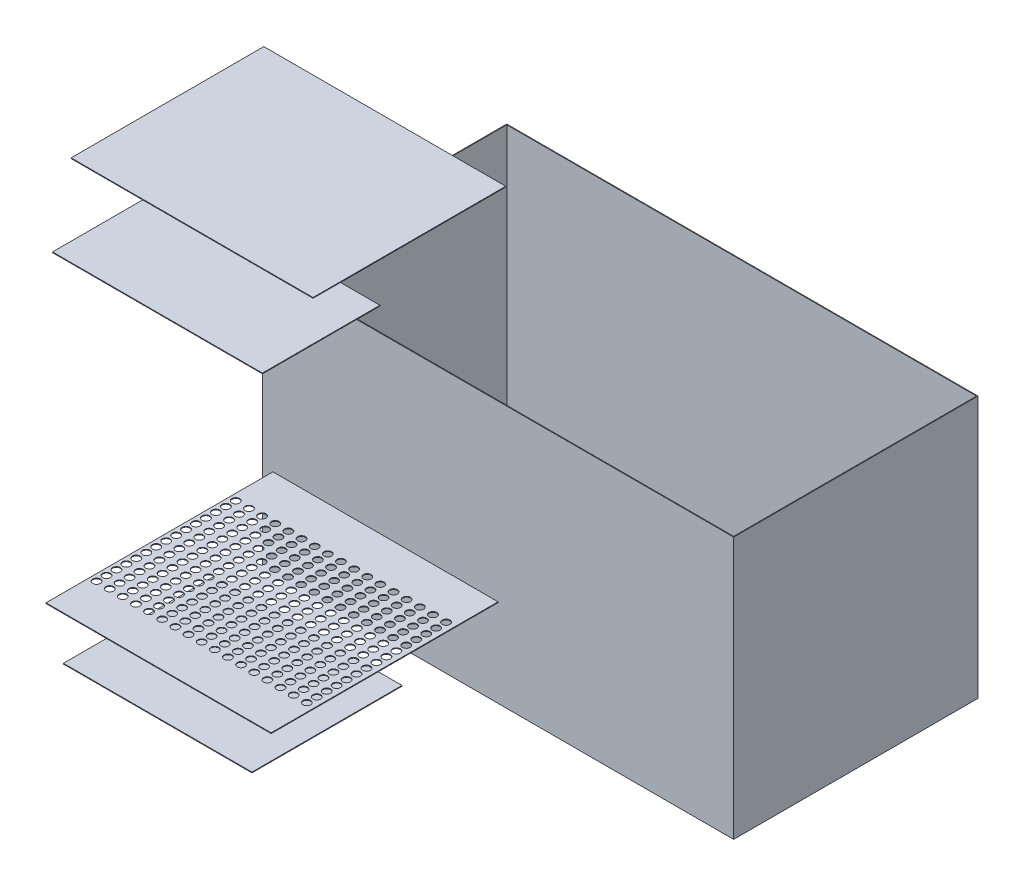
SolidWorks part; units mm, degrees
ref_plane "Спереди" through (0, 0, 0) normal (0, 0, 1) x (1, 0, 0)
ref_plane "Сверху" through (0, 0, 0) normal (0, 1, 0) x (1, 0, 0)
ref_plane "Справа" through (0, 0, 0) normal (1, 0, 0) x (0, 0, -1)
sketch "MASTER_FOOTPRINT" plane through (0, 0, 0) normal (0, 1, 0) x (1, 0, 0)
  line L1 (0, 0) -> (1350, 0)
  line L2 (0, 0) -> (0, 700)
  line L3 (0, 700) -> (1350, 700)
  line L4 (1350, 0) -> (1350, 700)
  dimension "D1" = 1350
  dimension "D2" = 700
extrude "BATH_BASE_PLATE" add sketch "MASTER_FOOTPRINT" along normal blind 750
shell "BATH_SHELL_2MM" thickness 2
sketch "Эскиз1" plane through (0, 0, 0) normal (0, 1, 0) x (1, 0, 0)
  line L1 (80, -220) -> (620, -220)
  line L2 (80, -220) -> (80, -650)
  line L3 (80, -650) -> (620, -650)
  line L4 (620, -220) -> (620, -650)
extrude "INLET_IMPACT_BAFFLE" add sketch "Эскиз1" along normal blind 2 from offset 125 separate body
sketch "Эскиз2" plane through (0, 0, 0) normal (0, 1, 0) x (1, 0, 0)
  line L0 (2, 2) -> (1348, 2) construction
  line L1 (30, 2) -> (675, 2)
  line L2 (30, 2) -> (30, -650)
  line L3 (30, -650) -> (675, -650)
  line L4 (675, 2) -> (675, -650)
  circle A0 centre (48.8235, -125) radius 11
  circle A1 centre (48.8235, -153.5) radius 11
  circle A2 centre (48.8235, -182) radius 11
  circle A3 centre (48.8235, -210.5) radius 11
  circle A4 centre (48.8235, -239) radius 11
  circle A5 centre (48.8235, -267.5) radius 11
  circle A6 centre (48.8235, -296) radius 11
  circle A7 centre (48.8235, -324.5) radius 11
  circle A8 centre (48.8235, -353) radius 11
  circle A9 centre (48.8235, -381.5) radius 11
  circle A10 centre (48.8235, -410) radius 11
  circle A11 centre (48.8235, -438.5) radius 11
  circle A12 centre (48.8235, -467) radius 11
  circle A13 centre (48.8235, -495.5) radius 11
  circle A14 centre (48.8235, -524) radius 11
  circle A15 centre (86.4706, -125) radius 11
  circle A16 centre (86.4706, -153.5) radius 11
  circle A17 centre (86.4706, -182) radius 11
  circle A18 centre (86.4706, -210.5) radius 11
  circle A19 centre (86.4706, -239) radius 11
  circle A20 centre (86.4706, -267.5) radius 11
  circle A21 centre (86.4706, -296) radius 11
  circle A22 centre (86.4706, -324.5) radius 11
  circle A23 centre (86.4706, -353) radius 11
  circle A24 centre (86.4706, -381.5) radius 11
  circle A25 centre (86.4706, -410) radius 11
  circle A26 centre (86.4706, -438.5) radius 11
  circle A27 centre (86.4706, -467) radius 11
  circle A28 centre (86.4706, -495.5) radius 11
  circle A29 centre (86.4706, -524) radius 11
  circle A30 centre (124.1176, -125) radius 11
  circle A31 centre (124.1176, -153.5) radius 11
  circle A32 centre (124.1176, -182) radius 11
  circle A33 centre (124.1176, -210.5) radius 11
  circle A34 centre (124.1176, -239) radius 11
  circle A35 centre (124.1176, -267.5) radius 11
  circle A36 centre (124.1176, -296) radius 11
  circle A37 centre (124.1176, -324.5) radius 11
  circle A38 centre (124.1176, -353) radius 11
  circle A39 centre (124.1176, -381.5) radius 11
  circle A40 centre (124.1176, -410) radius 11
  circle A41 centre (124.1176, -438.5) radius 11
  circle A42 centre (124.1176, -467) radius 11
  circle A43 centre (124.1176, -495.5) radius 11
  circle A44 centre (124.1176, -524) radius 11
  circle A45 centre (161.7647, -125) radius 11
  circle A46 centre (161.7647, -153.5) radius 11
  circle A47 centre (161.7647, -182) radius 11
  circle A48 centre (161.7647, -210.5) radius 11
  circle A49 centre (161.7647, -239) radius 11
  circle A50 centre (161.7647, -267.5) radius 11
  circle A51 centre (161.7647, -296) radius 11
  circle A52 centre (161.7647, -324.5) radius 11
  circle A53 centre (161.7647, -353) radius 11
  circle A54 centre (161.7647, -381.5) radius 11
  circle A55 centre (161.7647, -410) radius 11
  circle A56 centre (161.7647, -438.5) radius 11
  circle A57 centre (161.7647, -467) radius 11
  circle A58 centre (161.7647, -495.5) radius 11
  circle A59 centre (161.7647, -524) radius 11
  circle A60 centre (199.4118, -125) radius 11
  circle A61 centre (199.4118, -153.5) radius 11
  circle A62 centre (199.4118, -182) radius 11
  circle A63 centre (199.4118, -210.5) radius 11
  circle A64 centre (199.4118, -239) radius 11
  circle A65 centre (199.4118, -267.5) radius 11
  circle A66 centre (199.4118, -296) radius 11
  circle A67 centre (199.4118, -324.5) radius 11
  circle A68 centre (199.4118, -353) radius 11
  circle A69 centre (199.4118, -381.5) radius 11
  circle A70 centre (199.4118, -410) radius 11
  circle A71 centre (199.4118, -438.5) radius 11
  circle A72 centre (199.4118, -467) radius 11
  circle A73 centre (199.4118, -495.5) radius 11
  circle A74 centre (199.4118, -524) radius 11
  circle A75 centre (237.0588, -125) radius 11
  circle A76 centre (237.0588, -153.5) radius 11
  circle A77 centre (237.0588, -182) radius 11
  circle A78 centre (237.0588, -210.5) radius 11
  circle A79 centre (237.0588, -239) radius 11
  circle A80 centre (237.0588, -267.5) radius 11
  circle A81 centre (237.0588, -296) radius 11
  circle A82 centre (237.0588, -324.5) radius 11
  circle A83 centre (237.0588, -353) radius 11
  circle A84 centre (237.0588, -381.5) radius 11
  circle A85 centre (237.0588, -410) radius 11
  circle A86 centre (237.0588, -438.5) radius 11
  circle A87 centre (237.0588, -467) radius 11
  circle A88 centre (237.0588, -495.5) radius 11
  circle A89 centre (237.0588, -524) radius 11
  circle A90 centre (274.7059, -125) radius 11
  circle A91 centre (274.7059, -153.5) radius 11
  circle A92 centre (274.7059, -182) radius 11
  circle A93 centre (274.7059, -210.5) radius 11
  circle A94 centre (274.7059, -239) radius 11
  circle A95 centre (274.7059, -267.5) radius 11
  circle A96 centre (274.7059, -296) radius 11
  circle A97 centre (274.7059, -324.5) radius 11
  circle A98 centre (274.7059, -353) radius 11
  circle A99 centre (274.7059, -381.5) radius 11
  circle A100 centre (274.7059, -410) radius 11
  circle A101 centre (274.7059, -438.5) radius 11
  circle A102 centre (274.7059, -467) radius 11
  circle A103 centre (274.7059, -495.5) radius 11
  circle A104 centre (274.7059, -524) radius 11
  circle A105 centre (312.3529, -125) radius 11
  circle A106 centre (312.3529, -153.5) radius 11
  circle A107 centre (312.3529, -182) radius 11
  circle A108 centre (312.3529, -210.5) radius 11
  circle A109 centre (312.3529, -239) radius 11
  circle A110 centre (312.3529, -267.5) radius 11
  circle A111 centre (312.3529, -296) radius 11
  circle A112 centre (312.3529, -324.5) radius 11
  circle A113 centre (312.3529, -353) radius 11
  circle A114 centre (312.3529, -381.5) radius 11
  circle A115 centre (312.3529, -410) radius 11
  circle A116 centre (312.3529, -438.5) radius 11
  circle A117 centre (312.3529, -467) radius 11
  circle A118 centre (312.3529, -495.5) radius 11
  circle A119 centre (312.3529, -524) radius 11
  circle A120 centre (350, -125) radius 11
  circle A121 centre (350, -153.5) radius 11
  circle A122 centre (350, -182) radius 11
  circle A123 centre (350, -210.5) radius 11
  circle A124 centre (350, -239) radius 11
  circle A125 centre (350, -267.5) radius 11
  circle A126 centre (350, -296) radius 11
  circle A127 centre (350, -324.5) radius 11
  circle A128 centre (350, -353) radius 11
  circle A129 centre (350, -381.5) radius 11
  circle A130 centre (350, -410) radius 11
  circle A131 centre (350, -438.5) radius 11
  circle A132 centre (350, -467) radius 11
  circle A133 centre (350, -495.5) radius 11
  circle A134 centre (350, -524) radius 11
  circle A135 centre (387.6471, -125) radius 11
  circle A136 centre (387.6471, -153.5) radius 11
  circle A137 centre (387.6471, -182) radius 11
  circle A138 centre (387.6471, -210.5) radius 11
  circle A139 centre (387.6471, -239) radius 11
  circle A140 centre (387.6471, -267.5) radius 11
  circle A141 centre (387.6471, -296) radius 11
  circle A142 centre (387.6471, -324.5) radius 11
  circle A143 centre (387.6471, -353) radius 11
  circle A144 centre (387.6471, -381.5) radius 11
  circle A145 centre (387.6471, -410) radius 11
  circle A146 centre (387.6471, -438.5) radius 11
  circle A147 centre (387.6471, -467) radius 11
  circle A148 centre (387.6471, -495.5) radius 11
  circle A149 centre (387.6471, -524) radius 11
  circle A150 centre (425.2941, -125) radius 11
  circle A151 centre (425.2941, -153.5) radius 11
  circle A152 centre (425.2941, -182) radius 11
  circle A153 centre (425.2941, -210.5) radius 11
  circle A154 centre (425.2941, -239) radius 11
  circle A155 centre (425.2941, -267.5) radius 11
  circle A156 centre (425.2941, -296) radius 11
  circle A157 centre (425.2941, -324.5) radius 11
  circle A158 centre (425.2941, -353) radius 11
  circle A159 centre (425.2941, -381.5) radius 11
  circle A160 centre (425.2941, -410) radius 11
  circle A161 centre (425.2941, -438.5) radius 11
  circle A162 centre (425.2941, -467) radius 11
  circle A163 centre (425.2941, -495.5) radius 11
  circle A164 centre (425.2941, -524) radius 11
  circle A165 centre (462.9412, -125) radius 11
  circle A166 centre (462.9412, -153.5) radius 11
  circle A167 centre (462.9412, -182) radius 11
  circle A168 centre (462.9412, -210.5) radius 11
  circle A169 centre (462.9412, -239) radius 11
  circle A170 centre (462.9412, -267.5) radius 11
  circle A171 centre (462.9412, -296) radius 11
  circle A172 centre (462.9412, -324.5) radius 11
  circle A173 centre (462.9412, -353) radius 11
  circle A174 centre (462.9412, -381.5) radius 11
  circle A175 centre (462.9412, -410) radius 11
  circle A176 centre (462.9412, -438.5) radius 11
  circle A177 centre (462.9412, -467) radius 11
  circle A178 centre (462.9412, -495.5) radius 11
  circle A179 centre (462.9412, -524) radius 11
  circle A180 centre (500.5882, -125) radius 11
  circle A181 centre (500.5882, -153.5) radius 11
  circle A182 centre (500.5882, -182) radius 11
  circle A183 centre (500.5882, -210.5) radius 11
  circle A184 centre (500.5882, -239) radius 11
  circle A185 centre (500.5882, -267.5) radius 11
  circle A186 centre (500.5882, -296) radius 11
  circle A187 centre (500.5882, -324.5) radius 11
  circle A188 centre (500.5882, -353) radius 11
  circle A189 centre (500.5882, -381.5) radius 11
  circle A190 centre (500.5882, -410) radius 11
  circle A191 centre (500.5882, -438.5) radius 11
  circle A192 centre (500.5882, -467) radius 11
  circle A193 centre (500.5882, -495.5) radius 11
  circle A194 centre (500.5882, -524) radius 11
  circle A195 centre (538.2353, -125) radius 11
  circle A196 centre (538.2353, -153.5) radius 11
  circle A197 centre (538.2353, -182) radius 11
  circle A198 centre (538.2353, -210.5) radius 11
  circle A199 centre (538.2353, -239) radius 11
  circle A200 centre (538.2353, -267.5) radius 11
  circle A201 centre (538.2353, -296) radius 11
  circle A202 centre (538.2353, -324.5) radius 11
  circle A203 centre (538.2353, -353) radius 11
  circle A204 centre (538.2353, -381.5) radius 11
  circle A205 centre (538.2353, -410) radius 11
  circle A206 centre (538.2353, -438.5) radius 11
  circle A207 centre (538.2353, -467) radius 11
  circle A208 centre (538.2353, -495.5) radius 11
  circle A209 centre (538.2353, -524) radius 11
  circle A210 centre (575.8824, -125) radius 11
  circle A211 centre (575.8824, -153.5) radius 11
  circle A212 centre (575.8824, -182) radius 11
  circle A213 centre (575.8824, -210.5) radius 11
  circle A214 centre (575.8824, -239) radius 11
  circle A215 centre (575.8824, -267.5) radius 11
  circle A216 centre (575.8824, -296) radius 11
  circle A217 centre (575.8824, -324.5) radius 11
  circle A218 centre (575.8824, -353) radius 11
  circle A219 centre (575.8824, -381.5) radius 11
  circle A220 centre (575.8824, -410) radius 11
  circle A221 centre (575.8824, -438.5) radius 11
  circle A222 centre (575.8824, -467) radius 11
  circle A223 centre (575.8824, -495.5) radius 11
  circle A224 centre (575.8824, -524) radius 11
  circle A225 centre (613.5294, -125) radius 11
  circle A226 centre (613.5294, -153.5) radius 11
  circle A227 centre (613.5294, -182) radius 11
  circle A228 centre (613.5294, -210.5) radius 11
  circle A229 centre (613.5294, -239) radius 11
  circle A230 centre (613.5294, -267.5) radius 11
  circle A231 centre (613.5294, -296) radius 11
  circle A232 centre (613.5294, -324.5) radius 11
  circle A233 centre (613.5294, -353) radius 11
  circle A234 centre (613.5294, -381.5) radius 11
  circle A235 centre (613.5294, -410) radius 11
  circle A236 centre (613.5294, -438.5) radius 11
  circle A237 centre (613.5294, -467) radius 11
  circle A238 centre (613.5294, -495.5) radius 11
  circle A239 centre (613.5294, -524) radius 11
  circle A240 centre (651.1765, -125) radius 11
  circle A241 centre (651.1765, -153.5) radius 11
  circle A242 centre (651.1765, -182) radius 11
  circle A243 centre (651.1765, -210.5) radius 11
  circle A244 centre (651.1765, -239) radius 11
  circle A245 centre (651.1765, -267.5) radius 11
  circle A246 centre (651.1765, -296) radius 11
  circle A247 centre (651.1765, -324.5) radius 11
  circle A248 centre (651.1765, -353) radius 11
  circle A249 centre (651.1765, -381.5) radius 11
  circle A250 centre (651.1765, -410) radius 11
  circle A251 centre (651.1765, -438.5) radius 11
  circle A252 centre (651.1765, -467) radius 11
  circle A253 centre (651.1765, -495.5) radius 11
  circle A254 centre (651.1765, -524) radius 11
extrude "DISTRIBUTOR_D22" add sketch "Эскиз2" along normal blind 2 from offset 250 separate body
sketch "Эскиз3" plane through (0, 0, 0) normal (0, 1, 0) x (1, 0, 0)
  line L0 (30, -650) -> (675, -650) construction
  line L1 (48.8235, -313.5) -> (650, -313.5)
  line L2 (48.8235, -313.5) -> (48.8235, -650)
  line L3 (48.8235, -650) -> (650, -650)
  line L4 (650, -313.5) -> (650, -650)
  circle A0 centre (48.8235, -324.5) radius 11 construction
extrude "OUTLET_SUBMERGED_BAFFLE" add sketch "Эскиз3" along normal blind 2 from offset 1130 separate body
sketch "Эскиз4" plane through (0, 0, 0) normal (0, 1, 0) x (1, 0, 0)
  line L1 (2, 2) -> (695, 2)
  line L2 (2, 2) -> (2, -550)
  line L3 (2, -550) -> (695, -550)
  line L4 (695, 2) -> (695, -550)
extrude "OVERFLOW_WEIR_Z550" add sketch "Эскиз4" along normal blind 2 from offset 1290 separate body
equation "\"AI_Q_Peak\"= 0.006"
equation "\"AI_B_Bath\"= 700"
equation "\"AI_L_Settle\"= 900"
equation "\"AI_L_Inlet\"= 250"
equation "\"AI_L_Outlet\"= 200"
equation "\"AI_L_Bath\"= 1350"
equation "\"AI_H_Water\"= 550"
equation "\"AI_H_Freeboard\"= 200"
equation "\"AI_H_Bath\"= 750"
equation "\"AI_Shell_Thickness\"= 2"
equation "\"AI_Inlet_DN\"= 100"
equation "\"AI_Weir_Width\"= 600"
equation "\"AI_Inlet_Baffle_Offset\"= 125"
equation "\"AI_Distributor_Open_Area\"= 0.28"
equation "\"AI_Distributor_Hole_Dia\"= 22"
equation "\"AI_Distributor_Blind_Zone\"= 110"
equation "\"AI_Outlet_Baffle_Depth\"= 250"
equation "\"AI_Screw_Diameter\"= 100"
equation "\"AI_Screw_Pitch\"= 100"
equation "\"AI_Screw_Angle\"= 30"
equation "\"AI_Screw_Rpm\"= 15"
equation "\"AI_Screw_Clearance\"= 5"
equation "\"AI_Liner_Thickness\"= 5"
equation "\"AI_Discharge_Height\"= 650"
equation "\"AI_Frame_Height\"= 500"
equation "\"D1@MASTER_FOOTPRINT\" = \"AI_L_Bath\""
equation "\"D2@MASTER_FOOTPRINT\" = \"AI_B_Bath\""
equation "\"D1@BATH_BASE_PLATE\" = \"AI_H_Bath\""
